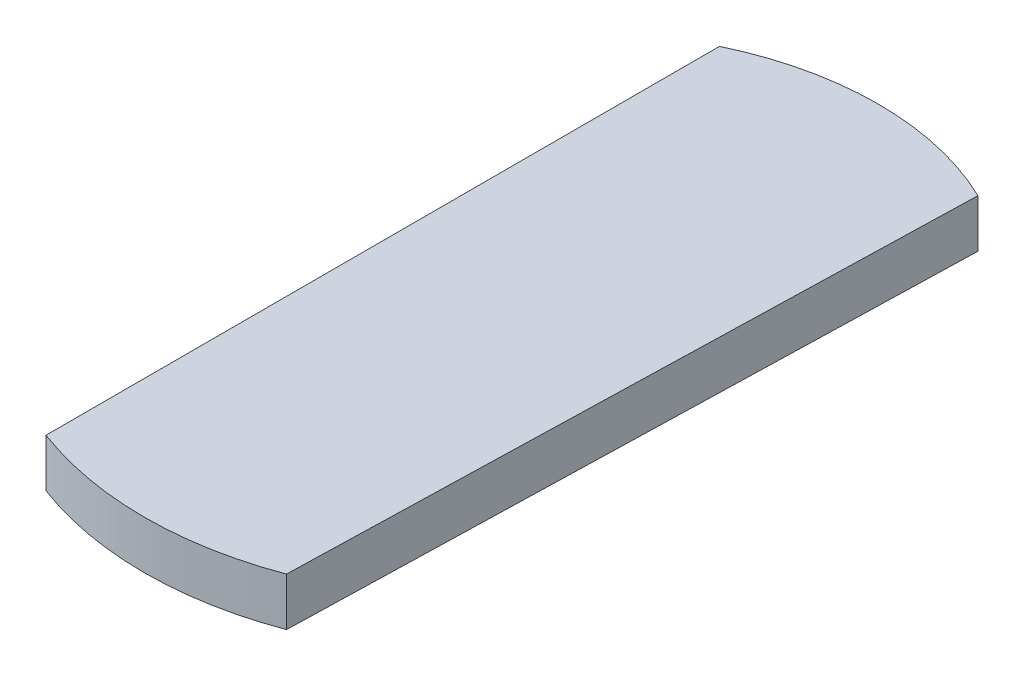
SolidWorks part; units mm, degrees
ref_plane "Front Plane" through (0, 0, 0) normal (0, 0, 1) x (1, 0, 0)
ref_plane "Top Plane" through (0, 0, 0) normal (0, 1, 0) x (1, 0, 0)
ref_plane "Right Plane" through (0, 0, 0) normal (1, 0, 0) x (0, 0, -1)
sketch "Sketch1" plane through (0, 0, 0) normal (0, 1, 0) x (1, 0, 0)
  line L0 (-9.2203, 62.7797) -> (-9.2203, -49.2203)
  line L2 (30.7797, -49.2203) -> (33.7797, 62.7797)
  arc A0 (-9.2203, 62.7797) -> (33.7797, 62.7797) centre (12.2797, 18.0834) cw
  arc A1 (-9.2203, -49.2203) -> (30.7797, -49.2203) centre (10.7797, 3.9815) ccw
  dimension "D1" = 112
  dimension "D2" = 43
  dimension "D3" = 40
extrude "Boss-Extrude2" add sketch "Sketch1" along normal blind 8
